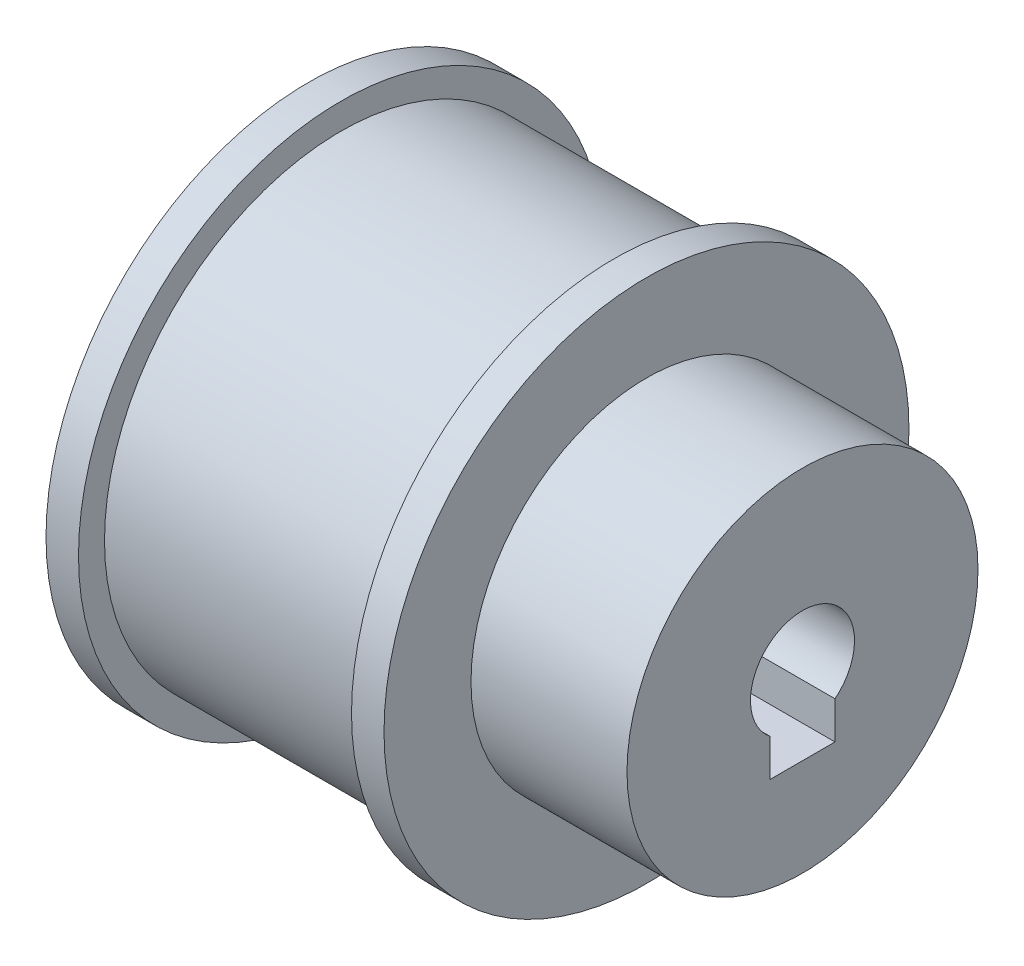
SolidWorks part; units mm, degrees
ref_plane "前视基准面" through (0, 0, 0) normal (0, 0, 1) x (1, 0, 0)
ref_plane "上视基准面" through (0, 0, 0) normal (0, 1, 0) x (1, 0, 0)
ref_plane "右视基准面" through (0, 0, 0) normal (1, 0, 0) x (0, 0, -1)
sketch "草图1" plane through (0, 0, 0) normal (0, 0, 1) x (1, 0, 0)
  line L0 (0, 0) -> (47.1, 0) construction
  line L1 (0, 0) -> (0, 20.19)
  line L2 (0, 20.19) -> (2.5, 20.19)
  line L3 (26, 20.19) -> (26, 13.5)
  line L4 (26, 13.5) -> (38, 13.5)
  line L5 (38, 13.5) -> (38, 0)
  line L6 (38, 0) -> (0, 0)
  line L7 (2.5, 20.19) -> (2.5, 18.19)
  line L8 (2.5, 18.19) -> (23.5, 18.19)
  line L9 (23.5, 18.19) -> (23.5, 20.19)
  line L10 (23.5, 20.19) -> (26, 20.19)
  dimension "D1" = 27
  dimension "D2" = 26
  dimension "D3" = 2
  dimension "D4" = 21
  dimension "D5" = 36.38
  dimension "D6" = 38
revolve "旋转1" add sketch "草图1" angle 360 about L0
sketch "草图2" plane through (38, 0, 0) normal (1, 0, 0) x (0, 0, -1)
  line L0 (0, 0) -> (0, -10.4757) construction
  line L2 (-2.5, -3.1225) -> (-2.5, -6)
  line L3 (-2.5, -6) -> (2.5, -6)
  line L4 (2.5, -3.1225) -> (2.5, -6)
  arc A0 (2.5, -3.1225) -> (-2.5, -3.1225) centre (0, 0) ccw
  dimension "D2" = 8
  dimension "D1" = 10
  dimension "D3" = 5
extrude "切除-拉伸1" cut sketch "草图2" against normal through all
